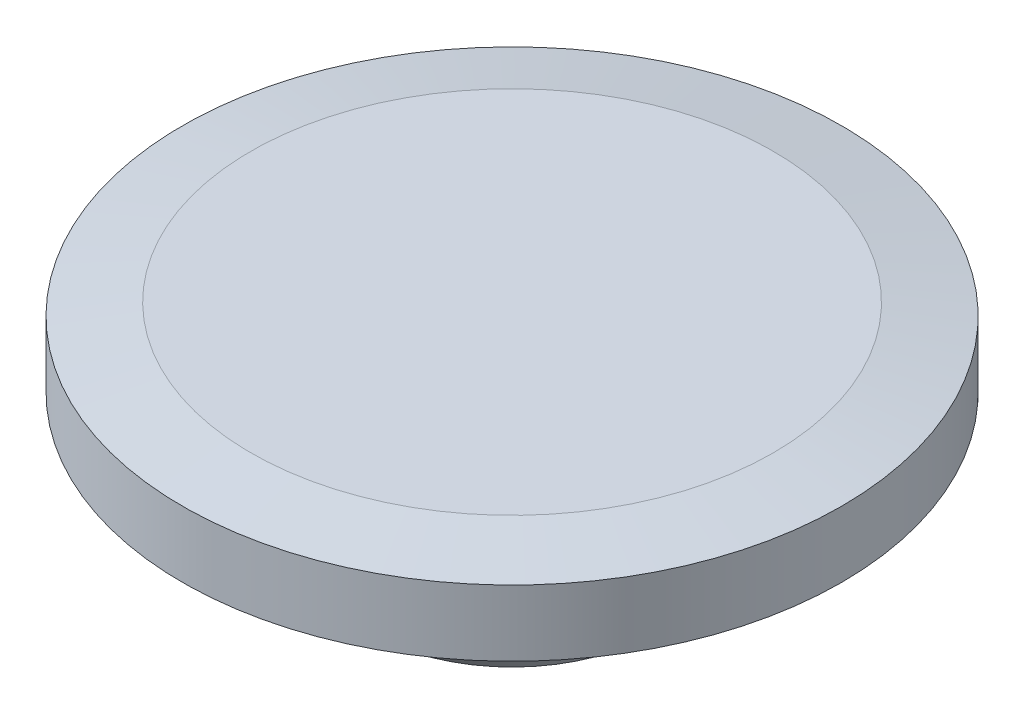
SolidWorks part; units mm, degrees
material "ABS"
ref_plane "Front Plane" through (0, 0, 0) normal (0, 0, 1) x (1, 0, 0)
ref_plane "Top Plane" through (0, 0, 0) normal (0, 1, 0) x (1, 0, 0)
ref_plane "Right Plane" through (0, 0, 0) normal (1, 0, 0) x (0, 0, -1)
sketch "Sketch1" plane through (0, 0, 0) normal (0, 0, 1) x (1, 0, 0)
  line L0 (-19, 4.8054) -> (-15.0608, 5.5)
  line L1 (-10.35, 0) -> (-19, 0)
  line L2 (0, -1.6) -> (0, 5.5)
  line L3 (0, 5.5) -> (-15.0608, 5.5)
  line L4 (-19, 0) -> (-19, 4.8054)
  line L6 (-5.6, 3.4) -> (-3, 3.4)
  line L12 (-8.6, -0.35) -> (-8.6, -6.85)
  line L13 (-8.6, -6.85) -> (-5.6, -6.85)
  line L14 (-5.6, -6.85) -> (-5.6, 3.4)
  line L15 (-10.35, 0) -> (-10.35, -0.35)
  line L16 (-10.35, -0.35) -> (-8.6, -0.35)
  line L20 (-3, 3.4) -> (-3, -1.6)
  line L21 (-3, -1.6) -> (0, -1.6)
  dimension "D5" = 5.5
  dimension "D6" = 4
  dimension "D7" = 10
  dimension "D1" = 5.6
  dimension "D4" = 19
  dimension "D9" = 0.35
  dimension "D10" = 1.75
  dimension "D2" = 10.25
  dimension "D8" = 6.5
  dimension "D11" = 3
  dimension "D12" = 5
  dimension "Bearing ID" = 8.6
revolve "Revolve1" add sketch "Sketch1" angle 360 about L2
chamfer "Chamfer2" distance 1 angle 83 1 edges at (19, 0, 0)
sketch "Sketch2" plane through (0, -1.6, 0) normal (0, -1, 0) x (1, 0, 0)
  line L6 (-5.85, 1.85) -> (-6.6, 1.1)
  line L7 (-0.35, -1.85) -> (-5.85, -1.85)
  line L8 (0.4, -1.1) -> (0.4, 1.1)
  line L9 (-0.35, 1.85) -> (-5.85, 1.85)
  line L10 (-6.6, -1.1) -> (-6.6, 1.1)
  line L11 (0.4, -1.85) -> (-6.6, 1.85) construction
  line L12 (0.4, 1.85) -> (-6.6, -1.85) construction
  line L13 (-5.85, -1.85) -> (-6.6, -1.1)
  line L14 (0.4, -1.1) -> (-0.35, -1.85)
  line L15 (0.4, 1.1) -> (-0.35, 1.85)
  circle A0 centre (0, 0) radius 8.6 construction
  circle A1 centre (0, 0) radius 8.6 construction
  point P0 (-3.1, 0)
  point P15 (-8.6, 0)
  circle M4 centre (0, 0) radius 3
  dimension "D2" = 3.7
  dimension "D1" = 7
  dimension "D3" = 2
extrude "Cut-Extrude1" cut sketch "Sketch2" against normal up to surface (5 mm away) and the other way through all contours L8 L15 L9 L7 L14 M4 | L13 L7 L9 L6 L10 M4 up to face at (3, 3.4, 0)
sketch "Sketch5" plane through (0, 0, 0) normal (0, 1, 0) x (1, 0, 0)
  circle A0 centre (-19, 0) radius 0.125
  circle A1 centre (0, 0) radius 19 construction
  circle A2 centre (19, 0) radius 0.125
  circle A3 centre (0, 19) radius 0.125
  circle A4 centre (0, -19) radius 0.125
  dimension "D1" = 0.25
extrude "Cut-Extrude2" [suppressed] cut sketch "Sketch5" against normal through all both and the other way through all contours A0
chamfer "Chamfer1" distance 1 angle 45 1 edges at (5.6, -6.85, 0)
chamfer "Chamfer3" distance 0.5 angle 30 1 edges at (8.6, -6.85, 0)
equation "\"BearingID\"=8.6"
equation "\"Bearing ID@Sketch1\"=\"BearingID\""
